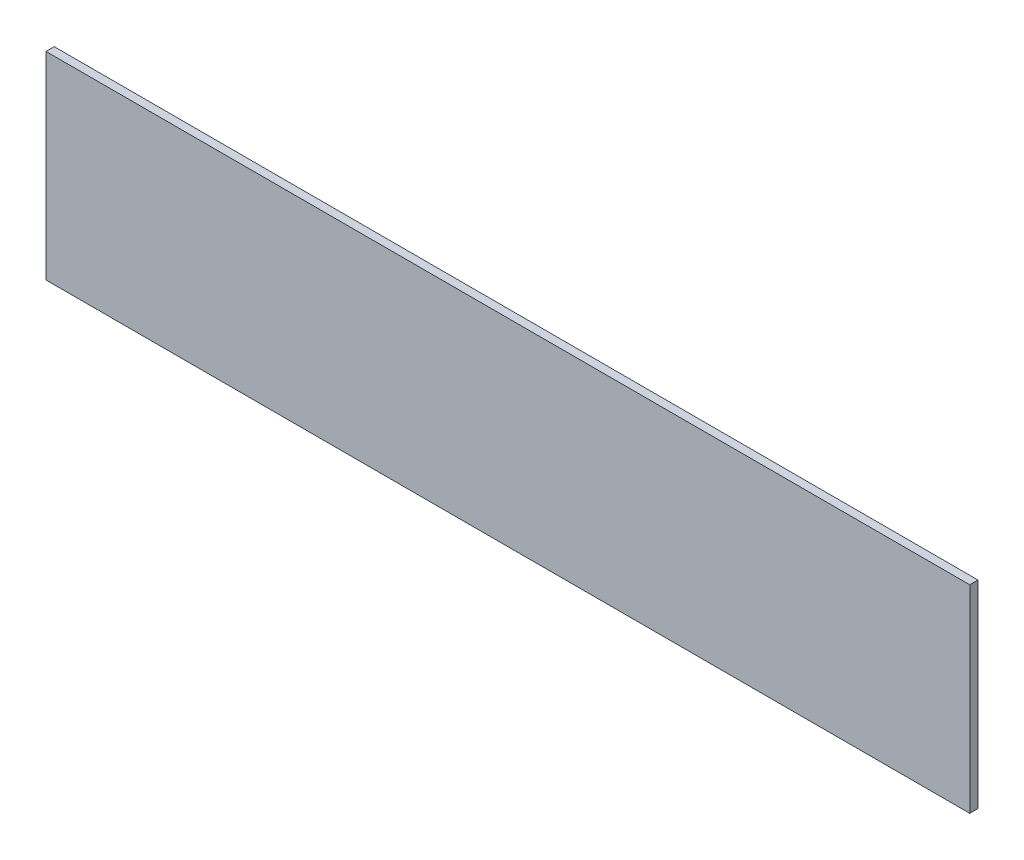
SolidWorks part; units mm, degrees
material "A-Glass Fiber"
ref_plane "Front Plane" through (0, 0, 0) normal (0, 0, 1) x (1, 0, 0)
ref_plane "Top Plane" through (0, 0, 0) normal (0, 1, 0) x (1, 0, 0)
ref_plane "Right Plane" through (0, 0, 0) normal (1, 0, 0) x (0, 0, -1)
sketch "Sketch1" plane through (0, 0, 0) normal (0, 0, 1) x (1, 0, 0)
  line L1 (0, 0) -> (177.8, 0)
  line L2 (0, 0) -> (0, 38.1)
  line L3 (0, 38.1) -> (177.8, 38.1)
  line L4 (177.8, 0) -> (177.8, 38.1)
  dimension "D1" = 177.8
  dimension "D2" = 38.1
extrude "Boss-Extrude1" add sketch "Sketch1" along normal blind 1.5875
